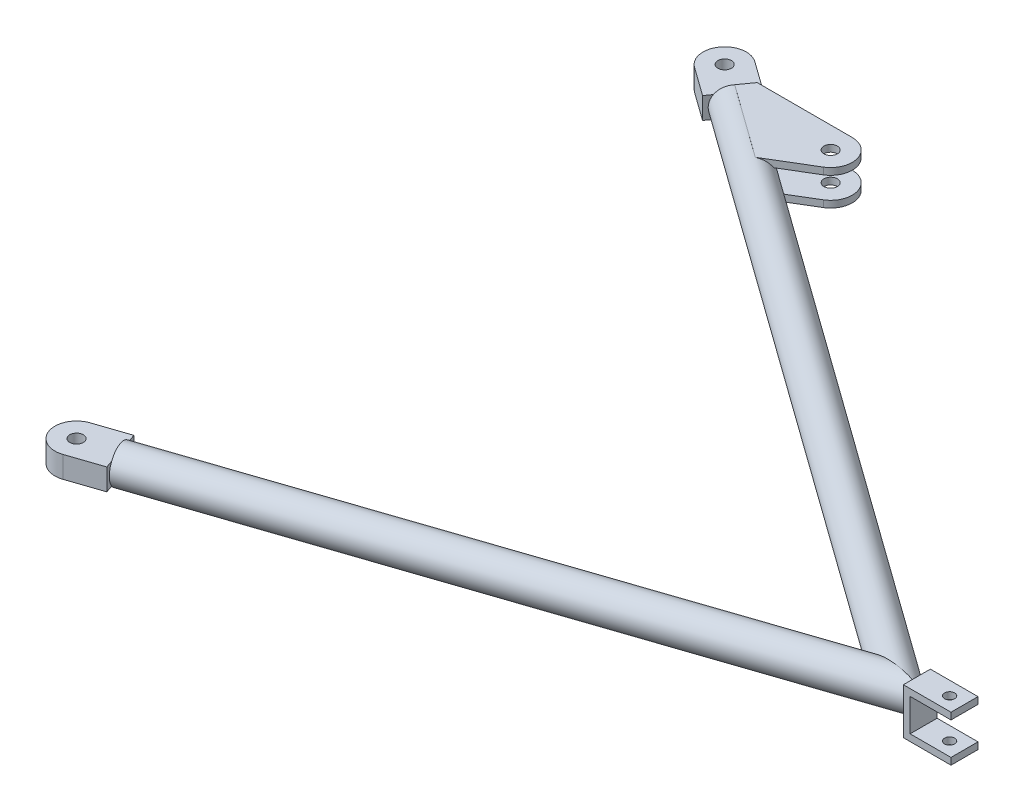
SolidWorks part; units mm, degrees
ref_plane "Front Plane" through (0, 0, 0) normal (0, 0, 1) x (1, 0, 0)
ref_plane "Top Plane" through (0, 0, 0) normal (0, 1, 0) x (1, 0, 0)
ref_plane "Right Plane" through (0, 0, 0) normal (1, 0, 0) x (0, 0, -1)
sketch "Sketch1" plane through (0, 0, 0) normal (0, 1, 0) x (1, 0, 0)
  line L0 (-288.83, -97.3667) -> (0, 0)
  line L1 (0, 0) -> (-288.83, 207.4333)
  line L2 (-288.83, 207.4333) -> (-288.83, -97.3667) construction
  dimension "D1" = 304.8
  dimension "D2" = 355.6
  dimension "D3" = 304.8
ref_plane "Plane1" through (-288.83, 0, 97.3667) normal (0.9476, 0, -0.3194) x (-0.3194, 0, -0.9476)
sketch "Sketch2" plane through (-288.83, 0, 97.3667) normal (0.9476, 0, -0.3194) x (-0.3194, 0, -0.9476)
  circle A0 centre (0, 0) radius 8.255
  dimension "D1" = 16.51
sweep "Sweep1" add profiles "Sketch2" path "Sketch1"
sketch "Sketch3" plane through (0, 0, 0) normal (0, 0, 1) x (1, 0, 0)
  line L0 (33.9318, 10.795) -> (11.5358, 10.795)
  line L1 (11.5358, 10.795) -> (11.5358, -10.795)
  line L2 (11.5358, -10.795) -> (33.9318, -10.795)
  line L3 (33.9318, -10.795) -> (33.9318, -7.62)
  line L4 (33.9318, -7.62) -> (14.7108, -7.62)
  line L5 (14.7108, -7.62) -> (14.7108, 7.62)
  line L6 (14.7108, 7.62) -> (33.9318, 7.62)
  line L7 (33.9318, 7.62) -> (33.9318, 10.795)
  line L8 (17.8858, 0) -> (-17.8858, 0) construction
  ellipse E0 centre (0, 0) end of major axis (17.8858, 0) minor radius 8.255 construction
  ellipse E1 centre (0, 0) end of major axis (17.8858, 0) minor radius 8.255 construction
  point P21 (11.5358, 0)
  dimension "D1" = 3.175
  dimension "D2" = 15.24
  dimension "D3" = 3.175
  dimension "D4" = 6.35
extrude "Boss-Extrude1" add sketch "Sketch3" along normal blind 8.89 and the other way blind 3.81
sketch "Sketch4" plane through (-288.83, 0, 97.3667) normal (-0.9476, 0, 0.3194) x (0.3194, 0, 0.9476)
  line L1 (-10.16, 5.08) -> (10.16, 5.08)
  line L2 (-10.16, 5.08) -> (-10.16, -5.08)
  line L3 (-10.16, -5.08) -> (10.16, -5.08)
  line L4 (10.16, 5.08) -> (10.16, -5.08)
  line L5 (-10.16, 5.08) -> (10.16, -5.08) construction
  line L6 (-10.16, -5.08) -> (10.16, 5.08) construction
  circle A1 centre (0, 0) radius 8.255
  circle A2 centre (0, 0) radius 8.255 construction
  dimension "D2" = 20.32
  dimension "D3" = 10.16
  dimension "D1" = 0
extrude "Boss-Extrude2" add sketch "Sketch4" along normal blind 10.16 and the other way blind 16.256
sketch "Sketch5" plane through (-288.83, 0, -207.4333) normal (-0.8122, 0, -0.5833) x (-0.5833, 0, 0.8122)
  line L1 (-10.16, 5.08) -> (10.16, 5.08)
  line L2 (-10.16, 5.08) -> (-10.16, -5.08)
  line L3 (-10.16, -5.08) -> (10.16, -5.08)
  line L4 (10.16, 5.08) -> (10.16, -5.08)
  line L5 (-10.16, 5.08) -> (10.16, -5.08) construction
  line L6 (-10.16, -5.08) -> (10.16, 5.08) construction
  point P0 (0, 0)
  dimension "D1" = 20.32
  dimension "D2" = 10.16
extrude "Boss-Extrude3" add sketch "Sketch5" along normal blind 10.16 and the other way blind 16.51
sketch "Sketch6" plane through (0, 5.08, 0) normal (0, 1, 0) x (1, 0, 0)
  line L0 (-269.4934, 206.0548) -> (-291.1556, 221.6123) construction
  line L1 (-281.3467, 189.5502) -> (-303.009, 205.1077) construction
  line L2 (-303.009, 205.1077) -> (-291.1556, 221.6123) construction
  line L3 (-294.7567, 199.181) -> (-303.009, 205.1077)
  line L4 (-303.009, 205.1077) -> (-297.0823, 213.36)
  arc A0 (-297.0823, 213.36) -> (-294.7567, 199.181) centre (-288.83, 207.4333) ccw
extrude "Cut-Extrude1" cut sketch "Sketch6" against normal through all
ref_plane "Plane2" through (0, 0, 0) normal (-0.5833, 0, 0.8122) x (0.8122, 0, 0.5833)
ref_plane "Plane3" through (0, 0, 0) normal (0.3194, 0, 0.9476) x (0.9476, 0, -0.3194)
mirror "Mirror1" about plane through (0, 0, 0) normal (-0.5833, 0, 0.8122) of "Cut-Extrude1"
sketch "Sketch7" plane through (0, 5.08, 0) normal (0, 1, 0) x (1, 0, 0)
  line L0 (-270.1802, -101.8014) -> (-295.2121, -110.2399) construction
  line L1 (-276.6713, -82.5461) -> (-301.7032, -90.9846) construction
  line L2 (-295.2121, -110.2399) -> (-301.7032, -90.9846) construction
  line L3 (-285.5845, -106.9943) -> (-295.2121, -110.2399)
  line L4 (-295.2121, -110.2399) -> (-298.4577, -100.6122)
  arc A0 (-285.5845, -106.9943) -> (-298.4577, -100.6122) centre (-288.83, -97.3667) cw
extrude "Cut-Extrude2" cut sketch "Sketch7" against normal through all
mirror "Mirror2" about plane through (0, 0, 0) normal (0.3194, 0, 0.9476) of "Cut-Extrude2"
sketch "Sketch8" plane through (-288.83, 0, 97.3667) normal (-0.9476, 0, 0.3194) x (0.3194, 0, 0.9476)
  line L0 (6.5068, -5.08) -> (-6.5068, -5.08) construction
  line L1 (-6.5068, 5.08) -> (6.5068, 5.08) construction
  line L2 (6.5068, -5.08) -> (-6.5068, -5.08)
  line L3 (-6.5068, 5.08) -> (6.5068, 5.08)
  arc A0 (-6.5068, -5.08) -> (6.5068, -5.08) centre (0, 0) ccw construction
  arc A1 (6.5068, 5.08) -> (-6.5068, 5.08) centre (0, 0) ccw construction
  arc A2 (-6.5068, -5.08) -> (6.5068, -5.08) centre (0, 0) ccw
  arc A3 (6.5068, 5.08) -> (-6.5068, 5.08) centre (0, 0) ccw
extrude "Cut-Extrude3" cut sketch "Sketch8" against normal up to surface (16.256 mm away) up to face at (-270.6241, 0, 100.4847)
sketch "Sketch9" plane through (-288.83, 0, -207.4333) normal (-0.8122, 0, -0.5833) x (-0.5833, 0, 0.8122)
  line L0 (6.5068, -5.08) -> (-6.5068, -5.08) construction
  line L1 (-6.5068, 5.08) -> (6.5068, 5.08) construction
  line L2 (6.5068, -5.08) -> (-6.5068, -5.08)
  line L3 (-6.5068, 5.08) -> (6.5068, 5.08)
  arc A0 (-6.5068, -5.08) -> (6.5068, -5.08) centre (0, 0) ccw construction
  arc A1 (6.5068, 5.08) -> (-6.5068, 5.08) centre (0, 0) ccw construction
  arc A2 (-6.5068, -5.08) -> (6.5068, -5.08) centre (0, 0) ccw
  arc A3 (6.5068, 5.08) -> (-6.5068, 5.08) centre (0, 0) ccw
extrude "Cut-Extrude4" cut sketch "Sketch9" against normal up to surface (16.51 mm away) up to face at (-280.5361, 0, -190.6788)
sketch "Sketch10" plane through (0, 5.08, 0) normal (0, 1, 0) x (1, 0, 0)
  point P0 (-288.83, 207.4333)
  point P1 (-288.83, -97.3667)
hole_wizard "E (0.25) Diameter Hole1" positions "3DSketch1" profile "Sketch11" hole size "E" standard "ANSI Inch"
sketch3d "3DSketch1"
  point P0 (-288.83, 5.08, -207.4333)
  point P3 (-288.83, 5.08, 97.3667)
sketch "Sketch11" plane through (-288.83, 5.08, -207.4333) normal (1, 0, 0) x (0, 0, 1)
  line L0 (0, 0) -> (0, 20.9577)
  line L1 (0, 20.9577) -> (3.175, 19.05)
  line L2 (3.175, 19.05) -> (3.175, 0)
  line L5 (3.175, 0) -> (0, 0)
  line L10 (0, 20.9577) -> (-3.175, 19.05) construction
  line L11 (0, -6.35) -> (0, 107.95) construction
  dimension "Hole Dia." = 6.35
  dimension "Hole Depth" = 19.05
  dimension "Drill Angle" = 118
hole_wizard "3/16 (0.1875) Diameter Hole1" positions "Sketch12" profile "Sketch13" hole size "3/16" standard "ANSI Inch" end condition through all
sketch "Sketch12" plane through (0, 10.795, 0) normal (0, 1, 0) x (1, 0, 0)
  point P0 (26.9335, -2.54)
sketch "Sketch13" plane through (26.9335, 10.795, 2.54) normal (1, 0, 0) x (0, 0, 1)
  line L0 (0, 0) -> (0, 21.59)
  line L1 (0, 21.59) -> (2.3812, 21.59)
  line L2 (2.3812, 21.59) -> (2.3812, 0)
  line L5 (2.3812, 0) -> (0, 0)
  line L11 (0, -6.35) -> (0, 107.95) construction
  dimension "Thru Hole Dia." = 4.7625
  dimension "Thru Hole Depth" = 21.59
sketch "Sketch14" plane through (0, 0, 8.89) normal (0, 0, 1) x (1, 0, 0)
  line L1 (14.7108, 4.6953) -> (14.7108, -4.6953)
  line L2 (14.7108, 4.6953) -> (14.7108, -4.6953)
  ellipse E1 centre (0, 0) end of major axis (17.8858, 0) minor radius 8.255 (14.7108, -4.6953) -> (14.7108, 4.6953) ccw
  ellipse E2 centre (0, 0) end of major axis (17.8858, 0) minor radius 8.255 (14.7108, -4.6953) -> (14.7108, 4.6953) ccw
  dimension "D1" = 0
extrude "Cut-Extrude5" cut sketch "Sketch14" against normal through all
ref_point "Point1"
ref_point "Point2"
sketch3d "3DSketch2"
  line L0 (26.9335, 10.795, 2.54) -> (26.9335, -10.795, 2.54)
  circle A0 centre (26.9335, 10.795, 2.54) radius 2.3812 construction
  circle A1 centre (26.9335, 10.795, 2.54) radius 2.3812
  circle A2 centre (26.9335, -10.795, 2.54) radius 2.3812 construction
  circle A3 centre (26.9335, -10.795, 2.54) radius 2.3812
  point P2 (26.9335, 13.1762, 2.54)
  point P4 (26.9335, 13.1762, 2.54)
  point P7 (26.9335, -8.4138, 2.54)
  point P9 (26.9335, -8.4138, 2.54)
  point P10 (26.9335, 0, 2.54)
  point P11 (26.9335, 0, 2.54)
ref_point "Point3"
sketch "Sketch15" plane through (0, 0, 0) normal (0, 1, 0) x (1, 0, 0)
  line L0 (-270.6046, 204.5075) -> (-225.9006, 204.5075)
  line L1 (-233.5551, 177.8991) -> (-220.6698, 185.6375)
  line L3 (11.5358, 1.8785) -> (-270.6046, 204.5075) construction
  line L4 (-233.5551, 177.8991) -> (-240.632, 173.649)
  line L5 (-240.632, 173.649) -> (-283.5993, 204.5075)
  line L6 (-270.6046, 204.5075) -> (-283.5993, 204.5075)
  line L7 (-275.0264, 198.3506) -> (-270.6046, 204.5075)
  line L8 (-271.6244, 203.0875) -> (-279.2157, 192.5175) construction
  arc A0 (-225.9006, 204.5075) -> (-220.6698, 185.6375) centre (-225.9006, 194.3475) cw
  circle A2 centre (-225.9006, 194.3475) radius 3.175
  dimension "D2" = 10.16
  dimension "D3" = 6.35
  dimension "D1" = 44.704
  dimension "D4" = 8.255
extrude "Boss-Extrude4" add sketch "Sketch15" against normal blind 3.175 from offset 8.255 separate body contours A0 L0 L7 L5 L4 L1 A2
sketch "Sketch16" plane through (0, 0, 0) normal (0, 1, 0) x (1, 0, 0)
  line L0 (-275.0264, 198.3506) -> (-270.6046, 204.5075) construction
  line L1 (-275.0264, 198.3506) -> (-270.6046, 204.5075)
  line L5 (-225.9006, 204.5075) -> (-270.6046, 204.5075)
  line L6 (-233.5551, 177.8991) -> (-220.6698, 185.6375)
  line L7 (-240.632, 173.649) -> (-233.5551, 177.8991)
  line L8 (-283.5993, 204.5075) -> (-240.632, 173.649)
  line L9 (-270.6046, 204.5075) -> (-283.5993, 204.5075)
  line L10 (-225.9006, 204.5075) -> (-270.6046, 204.5075)
  line L11 (-233.5551, 177.8991) -> (-220.6698, 185.6375)
  line L12 (-240.632, 173.649) -> (-233.5551, 177.8991)
  line L13 (-283.5993, 204.5075) -> (-240.632, 173.649)
  line L14 (-270.6046, 204.5075) -> (-283.5993, 204.5075)
  circle A1 centre (-225.9006, 194.3475) radius 3.175
  circle A2 centre (-225.9006, 194.3475) radius 3.175
  arc A3 (-220.6698, 185.6375) -> (-225.9006, 204.5075) centre (-225.9006, 194.3475) ccw
  arc A4 (-220.6698, 185.6375) -> (-225.9006, 204.5075) centre (-225.9006, 194.3475) ccw
  dimension "D1" = 0
  dimension "D2" = 0
extrude "Boss-Extrude6" add sketch "Sketch16" along normal blind 3.175 from offset 8.255 separate body contours L11 A4 L10 L1 L13 L12 A2 offset against normal yes
sketch3d "3DSketch3"
  line L0 (-225.9006, 8.255, -194.3475) -> (-225.9006, -8.255, -194.3475)
  circle A0 centre (-225.9006, 8.255, -194.3475) radius 3.175 construction
  circle A1 centre (-225.9006, 8.255, -194.3475) radius 3.175
  circle A2 centre (-225.9006, -8.255, -194.3475) radius 3.175 construction
  circle A3 centre (-225.9006, -8.255, -194.3475) radius 3.175
  point P2 (-225.9006, 11.43, -194.3475)
  point P4 (-225.9006, 11.43, -194.3475)
  point P7 (-225.9006, -5.08, -194.3475)
  point P9 (-225.9006, -5.08, -194.3475)
  point P10 (-225.9006, 0, -194.3475)
ref_point "Point4"
